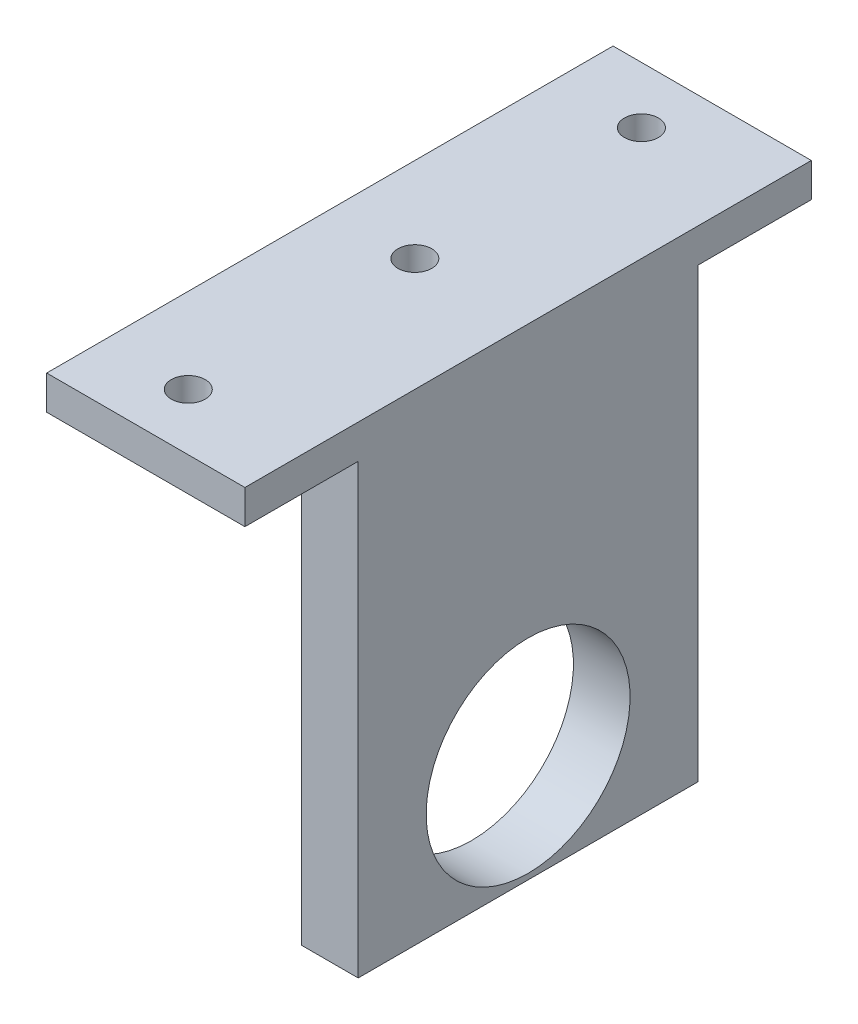
SolidWorks part; units mm, degrees
ref_plane "前视基准面" through (0, 0, 0) normal (0, 0, 1) x (1, 0, 0)
ref_plane "上视基准面" through (0, 0, 0) normal (0, 1, 0) x (1, 0, 0)
ref_plane "右视基准面" through (0, 0, 0) normal (1, 0, 0) x (0, 0, -1)
other "Configuration Table"
sketch "草图1" plane through (0, 0, 0) normal (1, 0, 0) x (0, 0, -1)
  line L0 (-15, -28.5) -> (-15, 11)
  line L2 (-15, 11) -> (15, 11)
  line L3 (15, -28.5) -> (15, 11)
  line L4 (-15, -28.5) -> (15, 11) construction
  line L5 (-15, 11) -> (15, -28.5) construction
  line L6 (-15, -28.5) -> (15, -28.5)
  point P0 (0, 0)
  point P2 (0, 0)
extrude "凸台-拉伸1" add sketch "草图1" along normal blind 5 contours L2 L3 L6 L0
sketch3d "3D草图1"
  point P0 (5, -2.7495, 2.7495)
ref_plane "基准面1" through (5, 0, 0) normal (1, 0, 0) x (0, 0, -1)
sketch "草图2" plane through (5, 0, 0) normal (1, 0, 0) x (0, 0, -1)
  circle A0 centre (0, -19) radius 9
extrude "切除-拉伸1" cut sketch "草图2" against normal blind 5
sketch3d "3D草图2"
  point P0 (2.9808, 11, -3.1847)
ref_plane "基准面2" through (0, 11, 0) normal (0, 1, 0) x (1, 0, 0)
sketch "草图3" plane through (0, 11, 0) normal (0, 1, 0) x (1, 0, 0)
  line L0 (5, -25) -> (5, 25)
  line L9 (5, -25) -> (-12.5, -25)
  line L10 (5, 25) -> (-12.5, 25)
  line L11 (-12.5, 25) -> (-12.5, -25)
  point P3 (5, 0)
extrude "凸台-拉伸2" add sketch "草图3" along normal blind 3
sketch3d "3D草图3"
  point P0 (-6.2094, 14, 4.3134)
ref_plane "基准面4" through (0, 14, 0) normal (0, 1, 0) x (1, 0, 0)
sketch "草图6" plane through (0, 14, 0) normal (0, 1, 0) x (1, 0, 0)
  circle A2 centre (-5, 0) radius 1.5
  circle A3 centre (-5, 20) radius 1.5
  circle A4 centre (-5, -20) radius 1.5
extrude "切除-拉伸2" cut sketch "草图6" against normal blind 3
